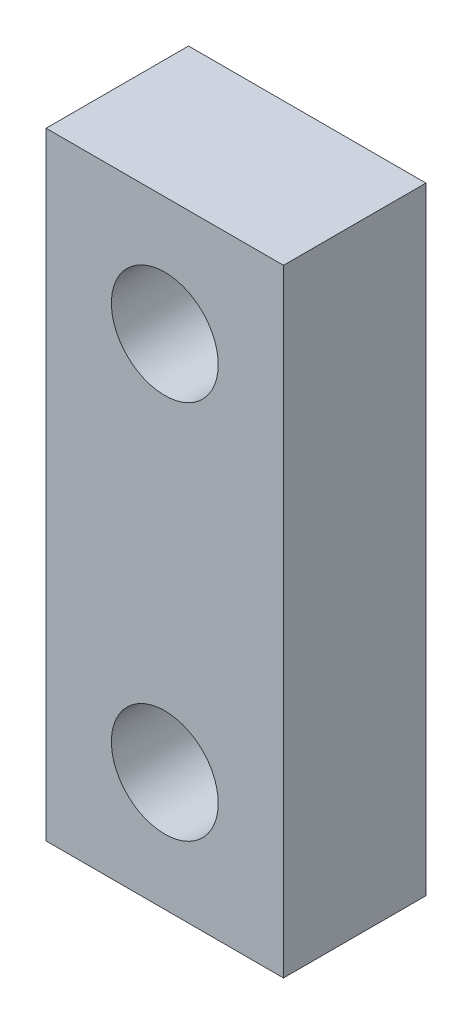
SolidWorks part; units mm, degrees
material "Printed PLA"
ref_plane "Front Plane" through (0, 0, 0) normal (0, 0, 1) x (1, 0, 0)
ref_plane "Top Plane" through (0, 0, 0) normal (0, 1, 0) x (1, 0, 0)
ref_plane "Right Plane" through (0, 0, 0) normal (1, 0, 0) x (0, 0, -1)
sketch "Sketch1" plane through (0, 0, 0) normal (0, 0, 1) x (1, 0, 0)
  line L0 (-5, 13) -> (5, -13) construction
  line L1 (-5, 13) -> (5, 13)
  line L2 (-5, 13) -> (-5, -13)
  line L3 (-5, -13) -> (5, -13)
  line L4 (5, 13) -> (5, -13)
  dimension "D1" = 26
  dimension "D2" = 10
extrude "Boss-Extrude1" add sketch "Sketch1" along normal blind 6
sketch "Sketch2" plane through (0, 0, 6) normal (0, 0, 1) x (1, 0, 0)
  line L0 (0, -8) -> (0, 8) construction
  circle A0 centre (0, 8) radius 2.25
  circle A1 centre (0, -8) radius 2.25
  dimension "D2" = 4.5
  dimension "D1" = 16
extrude "Cut-Extrude1" cut sketch "Sketch2" against normal through all
